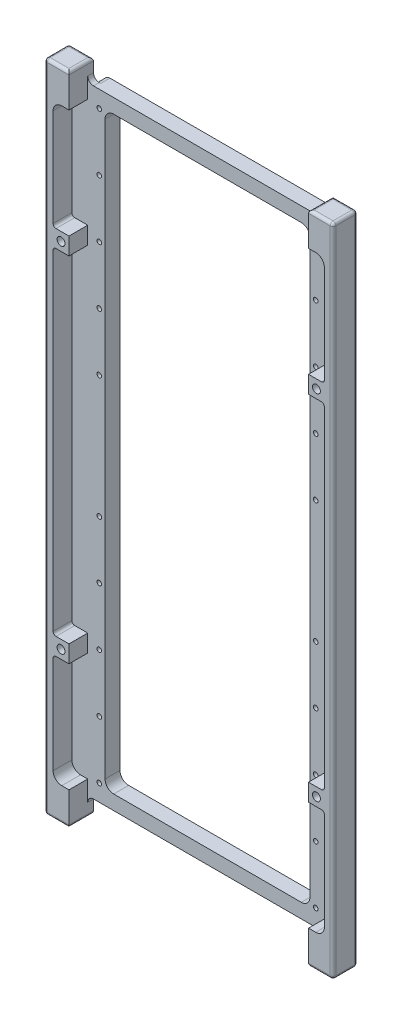
SolidWorks part; units mm, degrees
ref_plane "Front Plane" through (0, 0, 0) normal (0, 0, 1) x (1, 0, 0)
ref_plane "Top Plane" through (0, 0, 0) normal (0, 1, 0) x (1, 0, 0)
ref_plane "Right Plane" through (0, 0, 0) normal (1, 0, 0) x (0, 0, -1)
sketch "Sketch1" plane through (0, 0, 0) normal (0, 1, 0) x (1, 0, 0)
  line L1 (41.5, -4.25) -> (50, -4.25)
  line L2 (41.5, -4.25) -> (41.5, 4.25)
  line L3 (41.5, 4.25) -> (50, 4.25)
  line L4 (50, -4.25) -> (50, 4.25)
  line L5 (41.5, -4.25) -> (50, 4.25) construction
  line L6 (41.5, 4.25) -> (50, -4.25) construction
  point P0 (45.75, 0)
  dimension "D1" = 8.5
  dimension "D2" = 8.5
  dimension "D3" = 50
extrude "Boss-Extrude1" add sketch "Sketch1" along normal blind 227
sketch "Sketch2" plane through (41.5, 0, 0) normal (-1, 0, 0) x (0, 0, 1)
  line L0 (-4.25, 227) -> (-4.25, 0) construction
  line L1 (-4.25, 220.5) -> (-2.25, 220.5)
  line L2 (-4.25, 220.5) -> (-4.25, 6.5)
  line L3 (-4.25, 6.5) -> (-2.25, 6.5)
  line L4 (-2.25, 220.5) -> (-2.25, 6.5)
  line L5 (-4.25, 227) -> (4.25, 227) construction
  line L6 (-4.25, 0) -> (4.25, 0) construction
  point P6 (0, 227)
  dimension "D1" = 2
  dimension "D2" = 6.5
  dimension "D3" = 6.5
extrude "Boss-Extrude2" add sketch "Sketch2" along normal blind 50
mirror "Mirror2" about plane through (0, 0, 0) normal (1, 0, 0) of "Boss-Extrude1", "Boss-Extrude2"
sketch "Sketch3" plane through (0, 0, -4.25) normal (0, 0, -1) x (-1, 0, 0)
  line L0 (41.5, 220.5) -> (-41.5, 220.5) construction
  line L1 (-39, 6.5) -> (39, 6.5)
  line L2 (-41, 8.5) -> (-41, 218.5)
  line L3 (-39, 220.5) -> (39, 220.5)
  line L4 (41, 8.5) -> (41, 218.5)
  line L5 (-41, 6.5) -> (41, 220.5) construction
  line L6 (-41, 220.5) -> (41, 6.5) construction
  arc A0 (-39, 6.5) -> (-41, 8.5) centre (-39, 8.5) cw
  arc A1 (39, 6.5) -> (41, 8.5) centre (39, 8.5) ccw
  arc A2 (-41, 218.5) -> (-39, 220.5) centre (-39, 218.5) cw
  arc A3 (39, 220.5) -> (41, 218.5) centre (39, 218.5) cw
  point P0 (0, 113.5)
  dimension "D3" = 2
  dimension "D1" = 82
  dimension "D2" = 214
extrude "Boss-Extrude3" add sketch "Sketch3" along normal blind 3.18
sketch "Sketch4" plane through (0, 0, -7.43) normal (0, 0, -1) x (-1, 0, 0)
  line L0 (-39, 6.5) -> (39, 6.5) construction
  line L1 (-32.5, 11.5) -> (32.5, 11.5)
  line L2 (-35.5, 14.5) -> (-35.5, 212.5)
  line L3 (-32.5, 215.5) -> (32.5, 215.5)
  line L4 (35.5, 14.5) -> (35.5, 212.5)
  line L5 (-35.5, 11.5) -> (35.5, 215.5) construction
  line L6 (-35.5, 215.5) -> (35.5, 11.5) construction
  line L7 (39, 220.5) -> (-39, 220.5) construction
  line L8 (-41, 218.5) -> (-41, 8.5) construction
  line L9 (41, 8.5) -> (41, 218.5) construction
  arc A0 (-32.5, 11.5) -> (-35.5, 14.5) centre (-32.5, 14.5) cw
  arc A1 (32.5, 11.5) -> (35.5, 14.5) centre (32.5, 14.5) ccw
  arc A2 (32.5, 215.5) -> (35.5, 212.5) centre (32.5, 212.5) cw
  arc A3 (-35.5, 212.5) -> (-32.5, 215.5) centre (-32.5, 212.5) cw
  point P0 (0, 113.5)
  dimension "D1" = 3
  dimension "D2" = 5
  dimension "D3" = 5
  dimension "D4" = 5.5
  dimension "D5" = 5.5
extrude "Cut-Extrude1" cut sketch "Sketch4" against normal through all
fillet "Fillet1" radius 2 4 edges
fillet "Fillet2" radius 1 22 edges at (41.5, 227, 0) (45.75, 227, 4.25) (-41.5, 227, 0) (-50, 227, 0) (-50, 113.5, -4.25) (-45.75, 227, -4.25) (-45.75, 227, 4.25) (-50, 113.5, 4.25) (-50, 0, 0) (-45.75, 0, -4.25) (-41.5, 0, 0) (-45.75, 0, 4.25) (50, 227, 0) (45.75, 0, 4.25) (41.5, 0, 0) (45.75, 0, -4.25) (50, 0, 0) (45.75, 227, -4.25) (50, 113.5, 4.25) (50, 113.5, -4.25)
sketch "Sketch5" plane through (0, 0, 4.25) normal (0, 0, 1) x (1, 0, 0)
  line L0 (-39.5, 220.5) -> (39.5, 220.5) construction
  line L1 (-44, 11.5) -> (44, 11.5)
  line L2 (-47, 14.5) -> (-47, 48.3)
  line L3 (-44, 215.5) -> (44, 215.5)
  line L4 (47, 14.5) -> (47, 48.3)
  line L5 (-47, 11.5) -> (47, 215.5) construction
  line L6 (-47, 215.5) -> (47, 11.5) construction
  line L7 (-47, 113.5) -> (47, 113.5) construction
  line L8 (-46, 177.7) -> (-41.5, 177.7)
  line L9 (46, 171.7) -> (41.5, 171.7)
  line L10 (-46, 171.7) -> (-41.5, 171.7)
  line L11 (-41.5, 177.7) -> (-41.5, 171.7)
  line L14 (0, 215.5) -> (0, 11.5) construction
  line L15 (-47, 178.7) -> (-47, 212.5)
  line L16 (41.5, 177.7) -> (41.5, 171.7)
  line L17 (46, 177.7) -> (41.5, 177.7)
  line L18 (47, 178.7) -> (47, 212.5)
  line L19 (46, 49.3) -> (41.5, 49.3)
  line L20 (41.5, 49.3) -> (41.5, 55.3)
  line L21 (46, 55.3) -> (41.5, 55.3)
  line L22 (-46, 49.3) -> (-41.5, 49.3)
  line L23 (-41.5, 49.3) -> (-41.5, 55.3)
  line L24 (-46, 55.3) -> (-41.5, 55.3)
  line L25 (-47, 56.3) -> (-47, 170.7)
  line L26 (47, 56.3) -> (47, 170.7)
  arc A0 (-44, 11.5) -> (-47, 14.5) centre (-44, 14.5) cw
  arc A1 (44, 11.5) -> (47, 14.5) centre (44, 14.5) ccw
  arc A2 (44, 215.5) -> (47, 212.5) centre (44, 212.5) cw
  arc A3 (-47, 212.5) -> (-44, 215.5) centre (-44, 212.5) cw
  arc A4 (-46, 177.7) -> (-47, 178.7) centre (-46, 178.7) cw
  arc A5 (-47, 170.7) -> (-46, 171.7) centre (-46, 170.7) cw
  arc A6 (46, 177.7) -> (47, 178.7) centre (46, 178.7) ccw
  arc A7 (46, 171.7) -> (47, 170.7) centre (46, 170.7) cw
  arc A8 (46, 49.3) -> (47, 48.3) centre (46, 48.3) cw
  arc A9 (46, 55.3) -> (47, 56.3) centre (46, 56.3) ccw
  arc A10 (-46, 49.3) -> (-47, 48.3) centre (-46, 48.3) ccw
  arc A11 (-46, 55.3) -> (-47, 56.3) centre (-46, 56.3) cw
  point P0 (0, 113.5)
  point P42 (-47, 177.7)
  point P45 (-47, 171.7)
  point P48 (47, 177.7)
  point P51 (47, 171.7)
  point P54 (47, 49.3)
  point P57 (47, 55.3)
  point P60 (-47, 49.3)
  point P63 (-47, 55.3)
  dimension "D4" = 3
  dimension "D9" = 1
  dimension "D1" = 94
  dimension "D2" = 204
  dimension "D3" = 5
  dimension "D5" = 37.8
  dimension "D6" = 6
  dimension "D7" = 5.5
  dimension "D8" = 102
extrude "Cut-Extrude2" cut sketch "Sketch5" against normal blind 6.5
hole_wizard "M2x0.4 Tapped Hole1" positions "Sketch7" profile "Sketch6" tap size "M2x0.4" standard "ANSI Metric" end condition through all
sketch "Sketch7" plane through (0, 0, -7.43) normal (0, 0, -1) x (-1, 0, 0)
  line L0 (39, 220.5) -> (-39, 220.5) construction
  line L1 (-41, 218.5) -> (-41, 8.5) construction
  line L2 (-35.5, 113.5) -> (35.5, 113.5) construction
  line L3 (-35.5, 212.5) -> (-35.5, 14.5) construction
  line L4 (35.5, 14.5) -> (35.5, 212.5) construction
  point P0 (-37.5, 214.7)
  point P15 (37.5, 214.7)
  point P16 (37.5, 194.7)
  point P17 (37.5, 174.7)
  point P18 (37.5, 154.7)
  point P19 (37.5, 134.7)
  point P20 (-37.5, 194.7)
  point P21 (-37.5, 174.7)
  point P22 (-37.5, 154.7)
  point P23 (-37.5, 134.7)
  point P32 (-37.5, 12.3)
  point P33 (-37.5, 32.3)
  point P34 (-37.5, 52.3)
  point P35 (-37.5, 72.3)
  point P36 (-37.5, 92.3)
  point P37 (37.5, 92.3)
  point P38 (37.5, 72.3)
  point P39 (37.5, 52.3)
  point P40 (37.5, 32.3)
  point P41 (37.5, 12.3)
  dimension "D1" = 5.8
  dimension "D2" = 3.5
  dimension "D3" = 2
  dimension "D4" = 5
sketch "Sketch6" plane through (37.5, 214.7, -7.43) normal (1, 0, 0) x (0, 1, 0)
  line L0 (0, 0) -> (0, 11.68)
  line L1 (0, 11.68) -> (0.8, 11.68)
  line L2 (0.8, 11.68) -> (0.8, 0)
  line L5 (0.8, 0) -> (0, 0)
  line L11 (0, -6.35) -> (0, 107.95) construction
  dimension "Thread Major Dia." = 1.6
  dimension "Thru Tap Drill Depth" = 11.68
sketch "Sketch8" plane through (0, 0, -4.25) normal (0, 0, -1) x (-1, 0, 0)
  line L0 (-49, 227) -> (-42.5, 227) construction
  line L1 (-50, 1) -> (-50, 226) construction
  circle A0 centre (-44.25, 174.7) radius 1.375
  dimension "D1" = 2.75
  dimension "D2" = 52.3
  dimension "D3" = 5.75
extrude "Cut-Extrude3" cut sketch "Sketch8" against normal through all
sketch "Sketch9" plane through (0, 0, -4.25) normal (0, 0, -1) x (-1, 0, 0)
  circle A0 centre (-44.25, 174.7) radius 2.5
  dimension "D1" = 5
extrude "Cut-Extrude4" cut sketch "Sketch9" against normal blind 4.75
pattern_linear "LPattern1" count 2 spacing 88.5 along (-1, 0, 0) count 2 spacing 122.4 along (0, -1, 0) of "Cut-Extrude4", "Cut-Extrude3"
